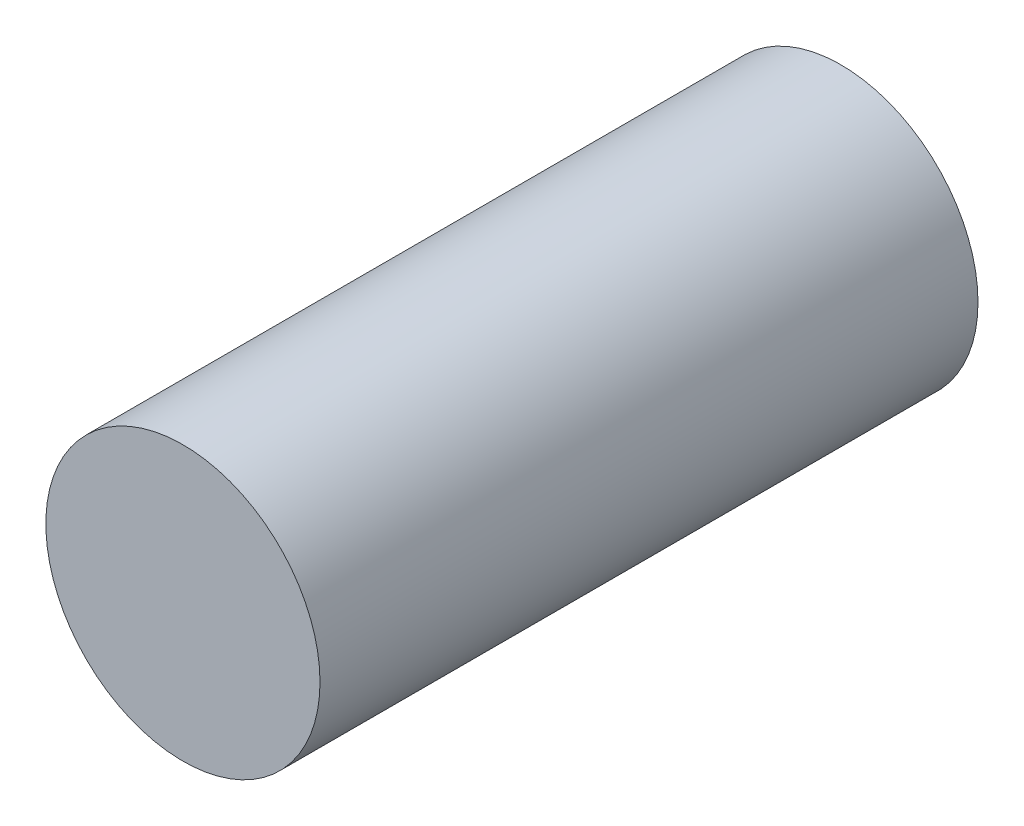
SolidWorks part; units mm, degrees
ref_plane "Front Plane" through (0, 0, 0) normal (0, 0, 1) x (1, 0, 0)
ref_plane "Top Plane" through (0, 0, 0) normal (0, 1, 0) x (1, 0, 0)
ref_plane "Right Plane" through (0, 0, 0) normal (1, 0, 0) x (0, 0, -1)
sketch "Sketch1" plane through (0, 0, 0) normal (0, 0, 1) x (1, 0, 0)
  circle A1 centre (0, 0) radius 6.25
  dimension "D1" = 12.5
extrude "Boss-Extrude1" add sketch "Sketch1" along normal mid plane 30
